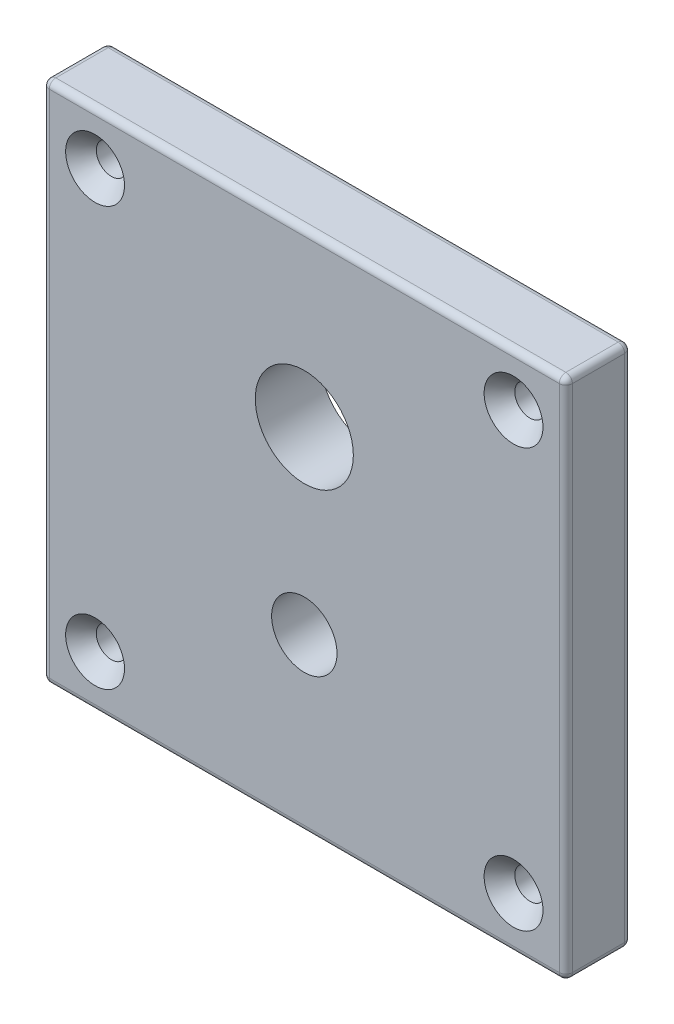
SolidWorks part; units mm, degrees
ref_plane "Front Plane" through (0, 0, 0) normal (1, 0, 0) x (0, 1, 0)
ref_plane "Top Plane" through (0, 0, 0) normal (0, 0, 1) x (0, 1, 0)
ref_plane "Right Plane" through (0, 0, 0) normal (0, 1, 0) x (-1, 0, 0)
sketch "Sketch1" plane through (0, 0, 0) normal (0, 0, 1) x (0, 1, 0)
  line L1 (-25.4, -25.4) -> (25.4, -25.4)
  line L2 (-25.4, -25.4) -> (-25.4, 25.4)
  line L3 (-25.4, 25.4) -> (25.4, 25.4)
  line L4 (25.4, -25.4) -> (25.4, 25.4)
  line L5 (-25.4, -25.4) -> (25.4, 25.4) construction
  line L6 (-25.4, 25.4) -> (25.4, -25.4) construction
  point P0 (0, 0)
  dimension "D1" = 50.8
extrude "Boss-Extrude1" add sketch "Sketch1" along normal blind 6.35
sketch "Sketch2" plane through (0, 0, 6.35) normal (0, 0, 1) x (1, 0, 0)
  line L0 (0, 25.4) -> (0, -25.4) construction
  line L1 (25.4, 25.4) -> (-25.4, 25.4) construction
  line L2 (-25.4, -25.4) -> (25.4, -25.4) construction
  line L3 (-25.4, 0) -> (25.4, 0) construction
  line L4 (-25.4, 25.4) -> (-25.4, -25.4) construction
  line L5 (25.4, -25.4) -> (25.4, 25.4) construction
  circle A0 centre (0, 8.7312) radius 4.7625
  circle A1 centre (0, -8.7313) radius 3.175
  dimension "D1" = 9.525
  dimension "D2" = 6.35
  dimension "D3" = 8.7312
  dimension "D4" = 8.7312
extrude "Cut-Extrude1" cut sketch "Sketch2" against normal up to next
sketch "Sketch5" plane through (0, 0, 6.35) normal (0, 0, 1) x (1, 0, 0)
  line L0 (-20.32, -20.32) -> (20.32, -20.32) construction
  line L5 (-20.32, 20.32) -> (-20.32, -20.32) construction
  line L6 (20.32, 20.32) -> (-20.32, 20.32) construction
  line L7 (-25.4, 0) -> (25.4, 0) construction
  line L8 (20.32, 20.32) -> (20.32, -20.32) construction
  line L9 (-25.4, 25.4) -> (-25.4, -25.4) construction
  line L10 (25.4, -25.4) -> (25.4, 25.4) construction
  line L11 (0, 25.4) -> (0, -25.4) construction
  line L12 (25.4, 25.4) -> (-25.4, 25.4) construction
  line L13 (-25.4, -25.4) -> (25.4, -25.4) construction
  circle A0 centre (-20.32, 20.32) radius 1.4732
  circle A1 centre (20.32, 20.32) radius 1.4732
  circle A2 centre (-20.32, -20.32) radius 1.4732
  circle A3 centre (20.32, -20.32) radius 1.4732
  point P0 (0, 0)
  dimension "D1" = 2.9464
  dimension "D2" = 20.32
  dimension "D3" = 20.32
  dimension "D4" = 20.32
  dimension "D5" = 20.32
extrude "Cut-Extrude2" cut sketch "Sketch5" against normal up to next
hole_wizard "CSK for #4 Flat Head Machine Screw1" positions "Sketch6" profile "Sketch7" countersink size "#4" standard "ANSI Inch" end condition through all
sketch "Sketch6" plane through (0, 0, 6.35) normal (0, 0, 1) x (1, 0, 0)
  point P0 (-20.32, 20.32)
  point P3 (20.32, 20.32)
  point P6 (20.32, -20.32)
  point P9 (-20.32, -20.32)
sketch "Sketch7" plane through (-20.32, 20.32, 6.35) normal (1, 0, 0) x (0, -1, 0)
  line L0 (0, 0) -> (0, 6.35)
  line L1 (0, 6.35) -> (1.4732, 6.35)
  line L2 (1.4732, 6.35) -> (1.4732, 1.5925)
  line L3 (1.4732, 1.5925) -> (2.8575, 0)
  line L5 (2.8575, 0) -> (0, 0)
  line L6 (-1.4732, 1.5925) -> (-2.8575, 0) construction
  line L11 (0, -6.35) -> (0, 107.95) construction
  dimension "Thru Hole Dia." = 2.9464
  dimension "Thru Hole Depth" = 6.35
  dimension "Near C'Sink Dia." = 5.715
  dimension "Near C'Sink Angle" = 82
fillet "Fillet1" radius 0.635 12 edges at (-25.4, 0, 6.35) (-25.4, 0, 0) (0, 25.4, 6.35) (-25.4, 25.4, 3.175) (0, 25.4, 0) (25.4, 0, 6.35) (25.4, 25.4, 3.175) (25.4, 0, 0) (-25.4, -25.4, 3.175) (0, -25.4, 6.35) (25.4, -25.4, 3.175) (0, -25.4, 0)
equation "\"N_pinion\"= 18"
equation "\"N_gear\"= 48"
equation "\"DP\"= 48"
equation "\"d_pinion\"= \"N_pinion\" / \"DP\""
equation "\"d_gear\"= \"N_gear\" / \"DP\""
equation "\"CD\"= ( \"d_pinion\" + \"d_gear\" ) / 2"
equation "\"bearing_L\"= 0.25"
equation "\"plate_t\"= \"bearing_L\""
equation "\"shaft_L\"= 1"
equation "\"cavity\"= \"shaft_L\" - 2 * \"plate_t\""
equation "\"plate_w\"= 2"
equation "\"screw_off\"= 0.2"
equation "\"bore_pinion\"= 0.25"
equation "\"bore_gear\"= 0.375"
equation "\"D_shaft_pinion\"= 0.125"
equation "\"D1@Sketch1\"=\"plate_w\""
equation "\"D1@Boss-Extrude1\"=\"plate_t\""
equation "\"D1@Sketch2\"=\"bore_gear\""
equation "\"D2@Sketch2\"=\"bore_pinion\""
equation "\"D3@Sketch2\"=\"CD\"/2"
equation "\"D4@Sketch2\"=\"CD\"/2"
equation "\"D2@Sketch5\"= \"plate_w\" / 2 - \"screw_off\""
equation "\"D3@Sketch5\"= \"plate_w\" / 2 - \"screw_off\""
equation "\"D4@Sketch5\"= \"plate_w\" / 2 - \"screw_off\""
equation "\"D5@Sketch5\"= \"plate_w\" / 2 - \"screw_off\""
